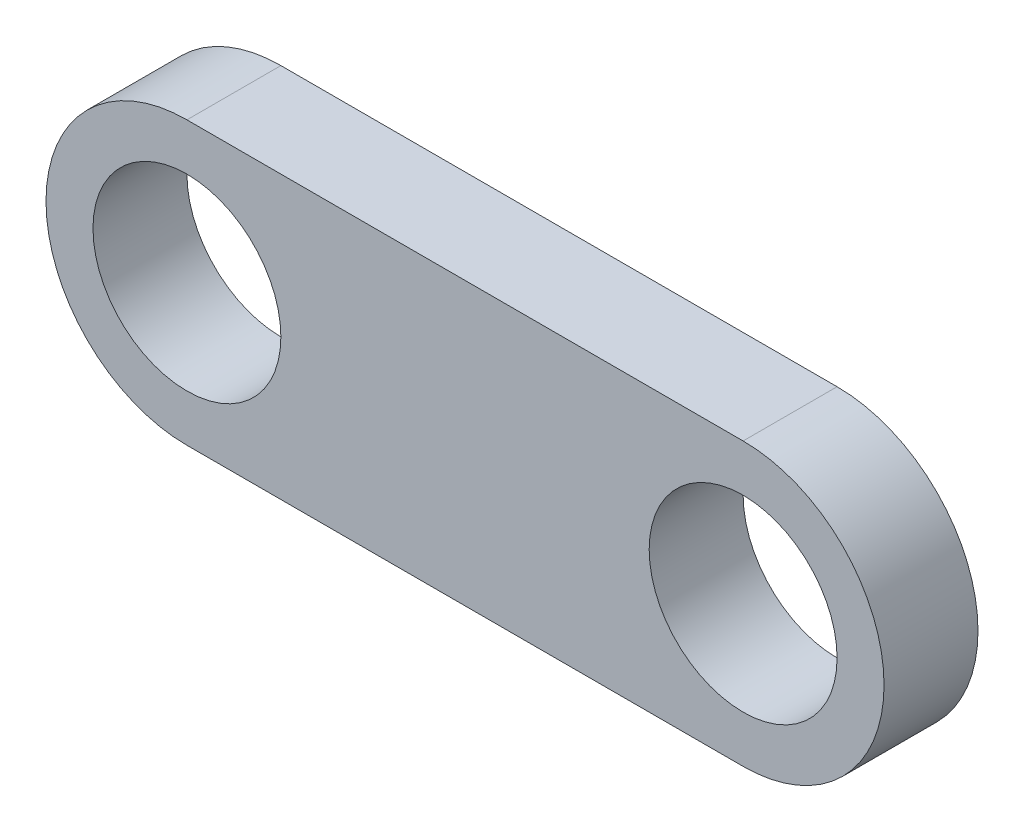
SolidWorks part; units mm, degrees
ref_plane "Front Plane" through (0, 0, 0) normal (0, 0, 1) x (1, 0, 0)
ref_plane "Top Plane" through (0, 0, 0) normal (0, 1, 0) x (1, 0, 0)
ref_plane "Right Plane" through (0, 0, 0) normal (1, 0, 0) x (0, 0, -1)
sketch "Sketch1" plane through (0, 0, 0) normal (0, 0, 1) x (1, 0, 0)
  line L0 (0, 0) -> (-5.92, 0) construction
  line L1 (0, -1.5) -> (-5.92, -1.5)
  line L2 (0, 1.5) -> (-5.92, 1.5)
  arc A0 (0, -1.5) -> (0, 1.5) centre (0, 0) ccw
  arc A1 (-5.92, 1.5) -> (-5.92, -1.5) centre (-5.92, 0) ccw
  circle A2 centre (-5.92, 0) radius 1
  circle A3 centre (0, 0) radius 1
  point P3 (-2.96, 0)
  dimension "D2" = 1.5
  dimension "D3" = 2
  dimension "D4" = 2
  dimension "D1" = 5.92
extrude "Boss-Extrude1" add sketch "Sketch1" along normal mid plane 1
